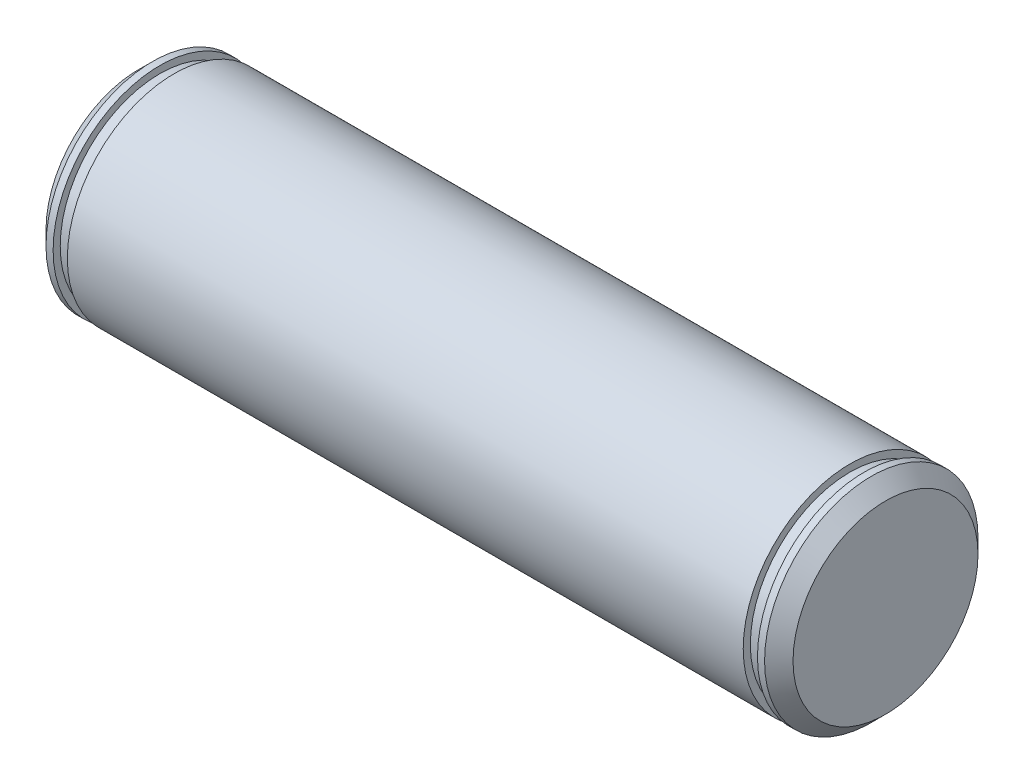
SolidWorks part; units mm, degrees
ref_plane "Front Plane" through (0, 0, 0) normal (0, 0, 1) x (1, 0, 0)
ref_plane "Top Plane" through (0, 0, 0) normal (0, 1, 0) x (1, 0, 0)
ref_plane "Right Plane" through (0, 0, 0) normal (1, 0, 0) x (0, 0, -1)
sketch "Sketch1" plane through (0, 0, 0) normal (0, 0, 1) x (1, 0, 0)
  line L0 (0, 0) -> (0, -38337.5161) construction
  line L1 (0, 0) -> (38337.5161, 0) construction
  line L2 (-52.5, 0) -> (52.5, 0)
  line L3 (52.5, 0) -> (52.5, 13)
  line L4 (-52.5, 0) -> (-52.5, 13)
  line L5 (50.5, 15) -> (49.5, 15)
  line L6 (-50.5, 15) -> (-49.5, 15)
  line L7 (49.5, 15) -> (49.5, 14)
  line L8 (-49.5, 15) -> (-49.5, 14)
  line L9 (49.5, 14) -> (47.5, 14)
  line L10 (-49.5, 14) -> (-47.5, 14)
  line L11 (47.5, 14) -> (47.5, 15)
  line L12 (-47.5, 14) -> (-47.5, 15)
  line L13 (47.5, 15) -> (-47.5, 15)
  line L14 (52.5, 13) -> (50.5, 15)
  line L15 (-52.5, 13) -> (-50.5, 15)
  point P5 (52.5, 15)
  point P8 (0, 0)
  point P9 (-52.5, 15)
  point P18 (0, 15)
  dimension "D1" = 105
  dimension "D2" = 30
  dimension "D3" = 28
  dimension "D4" = 2
  dimension "D5" = 3
  dimension "D6" = 2
  dimension "D7" = 45
  dimension "D8" = 2
  dimension "D9" = 45
revolve "Revolve1" add sketch "Sketch1" angle 360 about L1
